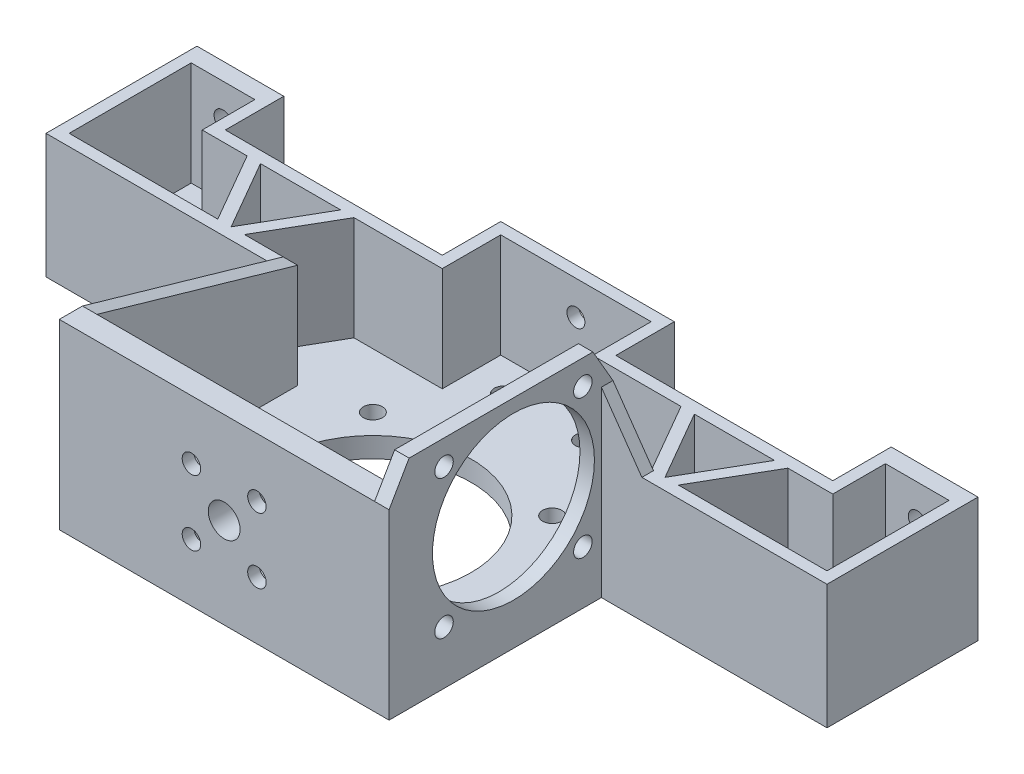
SolidWorks part; units mm, degrees
ref_plane "前视基准面" through (0, 0, 0) normal (0, 0, 1) x (1, 0, 0)
ref_plane "上视基准面" through (0, 0, 0) normal (0, 1, 0) x (1, 0, 0)
ref_plane "右视基准面" through (0, 0, 0) normal (1, 0, 0) x (0, 0, -1)
sketch "草图2" plane through (0, 0, 0) normal (0, 1, 0) x (1, 0, 0)
  line L15 (-39, 36.7) -> (-39, 62.8)
  line L16 (-39, 62.8) -> (-24, 62.8)
  line L17 (-24, 62.8) -> (-24, 52.7)
  line L18 (-24, 52.7) -> (13.5, 52.7)
  line L19 (13.5, 52.7) -> (13.5, 62.8)
  line L20 (13.5, 62.8) -> (43.5, 62.8)
  line L21 (43.5, 62.8) -> (43.5, 52.7)
  line L22 (43.5, 52.7) -> (81, 52.7)
  line L23 (81, 52.7) -> (81, 62.8)
  line L24 (81, 62.8) -> (96, 62.8)
  line L25 (96, 62.8) -> (96, 36.7)
  line L27 (-39, 36.7) -> (0, 36.7)
  line L28 (0, 36.7) -> (0, 0)
  line L29 (0, 0) -> (57, 0)
  line L30 (57, 0) -> (57, 36.7)
  line L31 (57, 36.7) -> (96, 36.7)
  line L32 (28.5, -43.9837) -> (28.5, 74.5213) construction
  line L33 (88.5, 80.2224) -> (88.5, -17.8161) construction
  line L34 (-31.5, 80.2224) -> (-31.5, -33.736) construction
  circle A1 centre (-31.5, 55.3) radius 1.6
  circle A3 centre (88.5, 55.3) radius 1.6
  circle A6 centre (21.5, 55.3) radius 1.6
  circle A7 centre (35.5, 55.3) radius 1.6
  circle A10 centre (28.5, 25.7) radius 17
  circle A11 centre (44, 41.2) radius 1.65
  circle A12 centre (44, 10.2) radius 1.65
  circle A13 centre (13, 10.2) radius 1.65
  circle A14 centre (13, 41.2) radius 1.65
  point P0 (-31.5, 55.3)
  point P1 (88.5, 55.3)
  point P2 (88.5, 80.2224)
  point P3 (-31.5, 80.2224)
  point P6 (21.5, 55.3)
  point P50 (28.5, 25.7)
  dimension "D2" = 120
  dimension "D20" = 3.2
  dimension "D22" = 34
  dimension "D7" = 25.7
  dimension "D10" = 57
  dimension "D11" = 27
  dimension "D14" = 3.3
  dimension "D17" = 31
  dimension "D3" = 60
  dimension "D4" = 14
  dimension "D5" = 7.5
  dimension "D6" = 28.5
  dimension "D8" = 16
  dimension "D9" = 30
  dimension "D12" = 15
  dimension "D13" = 15
  dimension "D16" = 4
  dimension "D19" = 28.5
extrude "凸台-拉伸2" add sketch "草图2" along normal blind 3.5
sketch "草图6" plane through (0, 3.5, 0) normal (0, 1, 0) x (1, 0, 0)
  line L9 (28.5, 25.7) -> (28.5, -10.253) construction
  line L12 (13.5, 52.7) -> (-24, 52.7) construction
  line L13 (13.5, 62.8) -> (13.5, 52.7) construction
  line L14 (43.5, 62.8) -> (13.5, 62.8) construction
  line L15 (43.5, 52.7) -> (43.5, 62.8) construction
  line L16 (81, 52.7) -> (43.5, 52.7) construction
  line L17 (81, 62.8) -> (81, 52.7) construction
  line L18 (96, 62.8) -> (81, 62.8) construction
  line L19 (96, 36.7) -> (96, 62.8) construction
  line L20 (57, 36.7) -> (96, 36.7) construction
  line L21 (57, 0) -> (57, 36.7) construction
  line L22 (0, 0) -> (57, 0) construction
  line L23 (0, 36.7) -> (0, 0) construction
  line L24 (-39, 36.7) -> (0, 36.7) construction
  line L25 (-39, 62.8) -> (-39, 36.7) construction
  line L26 (-24, 52.7) -> (-24, 62.8) construction
  line L27 (-24, 62.8) -> (-39, 62.8) construction
  line L28 (13.5, 52.7) -> (-24, 52.7)
  line L29 (13.5, 62.8) -> (13.5, 52.7)
  line L30 (43.5, 62.8) -> (13.5, 62.8)
  line L31 (43.5, 52.7) -> (43.5, 62.8)
  line L32 (81, 52.7) -> (43.5, 52.7)
  line L33 (81, 62.8) -> (81, 52.7)
  line L34 (96, 62.8) -> (81, 62.8)
  line L35 (96, 36.7) -> (96, 62.8)
  line L36 (57, 36.7) -> (96, 36.7)
  line L37 (57, 0) -> (57, 36.7)
  line L38 (0, 0) -> (57, 0)
  line L39 (0, 36.7) -> (0, 0)
  line L40 (-39, 36.7) -> (0, 36.7)
  line L41 (-39, 62.8) -> (-39, 36.7)
  line L42 (-24, 52.7) -> (-24, 62.8)
  line L43 (-24, 62.8) -> (-39, 62.8)
  line L44 (15.5, 50.7) -> (-26, 50.7)
  line L45 (-26, 50.7) -> (-26, 59.8)
  line L46 (-26, 59.8) -> (-37, 59.8)
  line L47 (-37, 59.8) -> (-37, 38.7)
  line L48 (-37, 38.7) -> (2.5, 38.7)
  line L49 (2.5, 38.7) -> (2.5, 4)
  line L50 (2.5, 4) -> (54.5, 4)
  line L51 (54.5, 4) -> (54.5, 38.7)
  line L52 (54.5, 38.7) -> (94, 38.7)
  line L53 (94, 38.7) -> (94, 59.8)
  line L54 (94, 59.8) -> (83, 59.8)
  line L55 (83, 59.8) -> (83, 50.7)
  line L56 (83, 50.7) -> (41.5, 50.7)
  line L57 (41.5, 50.7) -> (41.5, 60.8)
  line L58 (41.5, 60.8) -> (15.5, 60.8)
  line L59 (15.5, 60.8) -> (15.5, 50.7)
  dimension "D1" = 4
  dimension "D2" = 2
  dimension "D3" = 2
  dimension "D4" = 3
  dimension "D5" = 2
  dimension "D6" = 2
  dimension "D7" = 2
  dimension "D8" = 2
  dimension "D9" = 2
  dimension "D10" = 2
  dimension "D11" = 3
  dimension "D12" = 2
  dimension "D13" = 2
  dimension "D14" = 2.5
  dimension "D15" = 2.5
  dimension "D16" = 2
extrude "凸台-拉伸3" add sketch "草图6" along normal blind 18
sketch "草图11" plane through (0, 21.5, 0) normal (0, 1, 0) x (1, 0, 0)
  line L0 (2.5, 38.7) -> (2.5, 4)
  line L1 (2.5, 4) -> (54.5, 4)
  line L2 (54.5, 4) -> (54.5, 38.7)
  line L3 (54.5, 38.7) -> (57, 38.7)
  line L4 (54.5, 38.7) -> (94, 38.7) construction
  line L5 (57, 38.7) -> (57, 0)
  line L6 (57, 0) -> (57, 36.7) construction
  line L7 (57, 0) -> (0, 0)
  line L8 (0, 0) -> (0, 38.7)
  line L9 (-37, 38.7) -> (2.5, 38.7) construction
  line L10 (0, 38.7) -> (2.5, 38.7)
extrude "凸台-拉伸4" add sketch "草图11" along normal blind 10
sketch "草图12" plane through (0, 0, 0) normal (-1, 0, 0) x (0, 0, 1)
  line L0 (-38.7, 21.5) -> (-4, 31.5)
  line L1 (-38.7, 31.5) -> (0, 31.5) construction
  line L2 (-4, 31.5) -> (-38.7, 31.5)
  line L3 (-38.7, 31.5) -> (-38.7, 21.5)
  line L4 (0, 31.5) -> (0, 0) construction
  dimension "D1" = 4
extrude "切除-拉伸5" cut sketch "草图12" against normal blind 3
sketch "草图10" plane through (0, 0, 0) normal (0, 0, 1) x (1, 0, 0)
  line L0 (28.5, 37.2917) -> (28.5, -8.8083) construction
  line L5 (0, 0) -> (57, 0) construction
  line L6 (0, 31.5) -> (0, 0) construction
  line L7 (57, 31.5) -> (57, 0) construction
  circle A0 centre (28.5, 15.6569) radius 2.75
  circle A1 centre (34.1569, 21.3137) radius 1.6
  circle A2 centre (34.1569, 10) radius 1.6
  circle A3 centre (22.8431, 10) radius 1.6
  circle A4 centre (22.8431, 21.3137) radius 1.6
  point P19 (28.5, 15.6569)
  dimension "D1" = 10
  dimension "D2" = 5.5
  dimension "D3" = 3.2
  dimension "D4" = 8
  dimension "D5" = 4
extrude "切除-拉伸4" cut sketch "草图10" against normal blind 5
sketch "草图13" plane through (0, 3.5, 0) normal (0, 1, 0) x (1, 0, 0)
  line L0 (-15.9282, 50.7) -> (-9, 38.7)
  line L1 (15.5, 50.7) -> (-26, 50.7) construction
  line L2 (-37, 38.7) -> (0, 38.7) construction
  line L3 (-9, 38.7) -> (-2.0718, 50.7)
  line L5 (-15.9282, 50.7) -> (-18.2376, 50.7)
  line L6 (15.5, 50.7) -> (-26, 50.7) construction
  line L7 (-18.2376, 50.7) -> (-11.3094, 38.7)
  line L8 (-24, 52.7) -> (-24, 62.8) construction
  line L9 (-11.3094, 38.7) -> (-9, 38.7)
  line L10 (-2.0718, 50.7) -> (0.2376, 50.7)
  line L11 (0.2376, 50.7) -> (-6.6906, 38.7)
  line L12 (-6.6906, 38.7) -> (-9, 38.7)
  line L13 (-9, 38.7) -> (-9, 56.0294) construction
  line L14 (0, 38.7) -> (0, 4) construction
  line L15 (28.5, 62.8) -> (28.5, -17.4304) construction
  line L16 (43.5, 62.8) -> (13.5, 62.8) construction
  line L17 (63.6906, 38.7) -> (66, 38.7)
  line L18 (56.7624, 50.7) -> (63.6906, 38.7)
  line L19 (59.0718, 50.7) -> (56.7624, 50.7)
  line L20 (66, 38.7) -> (59.0718, 50.7)
  line L21 (68.3094, 38.7) -> (66, 38.7)
  line L22 (75.2376, 50.7) -> (68.3094, 38.7)
  line L23 (72.9282, 50.7) -> (75.2376, 50.7)
  line L24 (72.9282, 50.7) -> (66, 38.7)
  line M13 (15.5, 50.7) -> (-26, 50.7)
  line M17 (-37, 38.7) -> (2.5, 38.7)
  line M21 (54.5, 38.7) -> (94, 38.7)
  line M25 (83, 50.7) -> (41.5, 50.7)
  dimension "D1" = 2
  dimension "D2" = 60
  dimension "D3" = 15
  dimension "D4" = 9
extrude "凸台-拉伸5" add sketch "草图13" along normal up to surface (18 mm away) contours L7 L0 M13 M17 | L11 L3 M13 M17 | L20 L18 M21 M25 | L24 L22 M25 M21 up to face at (28.5, 21.5, -51.8857)
sketch "草图14" plane through (0, 0, -62.8) normal (0, 0, -1) x (-1, 0, 0)
  line L0 (-28.5, 46.072) -> (-28.5, -18.623) construction
  line L1 (39, 21.5) -> (39, 0) construction
  line L2 (-96, 21.5) -> (-96, 0) construction
  circle A0 centre (31.5, 15.6569) radius 1.55
  circle A1 centre (-88.5, 15.6569) radius 1.55
  circle A2 centre (-28.5, 15.6569) radius 1.55
  dimension "D1" = 3.1
  dimension "D2" = 120
  dimension "D4" = 3.1
extrude "切除-拉伸6" cut sketch "草图14" against normal blind 10
sketch "草图16" plane through (0, 0, 0) normal (-1, 0, 0) x (0, 0, 1)
  line L0 (-22.7, 26.111) -> (-22.7, 18.5)
  line L1 (-38.7, 21.5) -> (-4, 31.5) construction
  line L2 (-22.7, 18.5) -> (-38.7, 18.5)
  line L3 (-38.7, 21.5) -> (-38.7, 18.5)
  line L4 (-38.7, 21.5) -> (-22.7, 26.111)
  dimension "D1" = 16
  dimension "D2" = 3
sketch "草图20" plane through (0, 0, -4) normal (0, 0, -1) x (-1, 0, 0)
  line L0 (-25.8431, 19.5817) -> (-22.8431, 17.8496)
  line L1 (-32.4248, 18.3137) -> (-30.6928, 21.3137)
  line L2 (-30.6928, 21.3137) -> (-32.4248, 24.3137)
  line L3 (-32.4248, 24.3137) -> (-35.8889, 24.3137)
  line L4 (-35.8889, 24.3137) -> (-37.621, 21.3137)
  line L5 (-37.621, 21.3137) -> (-35.8889, 18.3137)
  line L6 (-35.8889, 18.3137) -> (-32.4248, 18.3137)
  line L7 (-22.8431, 17.8496) -> (-19.8431, 19.5817)
  line L8 (-19.8431, 19.5817) -> (-19.8431, 23.0458)
  line L9 (-19.8431, 23.0458) -> (-22.8431, 24.7778)
  line L10 (-22.8431, 24.7778) -> (-25.8431, 23.0458)
  line L11 (-25.8431, 23.0458) -> (-25.8431, 19.5817)
  line L12 (-24.5752, 13) -> (-26.3072, 10)
  line L13 (-26.3072, 10) -> (-24.5752, 7)
  line L14 (-24.5752, 7) -> (-21.1111, 7)
  line L15 (-21.1111, 7) -> (-19.379, 10)
  line L16 (-19.379, 10) -> (-21.1111, 13)
  line L17 (-21.1111, 13) -> (-24.5752, 13)
  line L18 (-31.1569, 11.7321) -> (-34.1569, 13.4641)
  line L19 (-34.1569, 13.4641) -> (-37.1569, 11.7321)
  line L20 (-37.1569, 11.7321) -> (-37.1569, 8.2679)
  line L21 (-37.1569, 8.2679) -> (-34.1569, 6.5359)
  line L22 (-34.1569, 6.5359) -> (-31.1569, 8.2679)
  line L23 (-31.1569, 8.2679) -> (-31.1569, 11.7321)
  circle A0 centre (-34.1569, 21.3137) radius 3 construction
  point P30 (-28.5, 15.6569)
  dimension "D1" = 6
  dimension "D2" = 4
extrude "切除-拉伸7" cut sketch "草图20" against normal blind 2
sketch "草图22" plane through (0, 0, -38.7) normal (0, 0, -1) x (-1, 0, 0)
  line L0 (-57, 31.5) -> (-64.0021, 21.5)
  line L1 (-81, 21.5) -> (-43.5, 21.5) construction
  line L2 (-64.0021, 21.5) -> (-57, 21.5)
  line L3 (-57, 21.5) -> (-57, 31.5)
  dimension "D1" = 35
extrude "凸台-拉伸6" add sketch "草图22" against normal up to surface (2 mm away) up to face at (76.5, 10.75, -36.7)
sketch "草图24" plane through (57, 0, 0) normal (1, 0, 0) x (0, 0, -1)
  line L0 (0, 31.5) -> (3.4641, 37.5)
  line L1 (3.4641, 37.5) -> (35.2359, 37.5)
  line L2 (35.2359, 37.5) -> (38.7, 31.5)
  line L3 (38.7, 31.5) -> (38.7, 21.5) construction
  line L4 (0, 31.5) -> (36.7, 31.5) construction
  line L5 (0, 31.5) -> (36.7, 31.5) construction
  line L6 (38.7, 31.5) -> (0, 31.5)
  dimension "D1" = 60
  dimension "D2" = 60
  dimension "D3" = 6
extrude "凸台-拉伸7" add sketch "草图24" against normal up to surface (2.5 mm away) up to face at (54.5, 17.5, -21.35)
sketch "草图21" plane through (57, 0, 0) normal (1, 0, 0) x (0, 0, -1)
  circle A8 centre (9.5, 33.2) radius 1.6
  circle A9 centre (33.5, 33.2) radius 1.6
  circle A10 centre (33.5, 9.2) radius 1.6
  circle A11 centre (9.5, 9.2) radius 1.6
  circle A12 centre (21.5, 21.2) radius 14
  dimension "D1" = 3.2
  dimension "D2" = 28
extrude "切除-拉伸8" cut sketch "草图21" against normal blind 3
